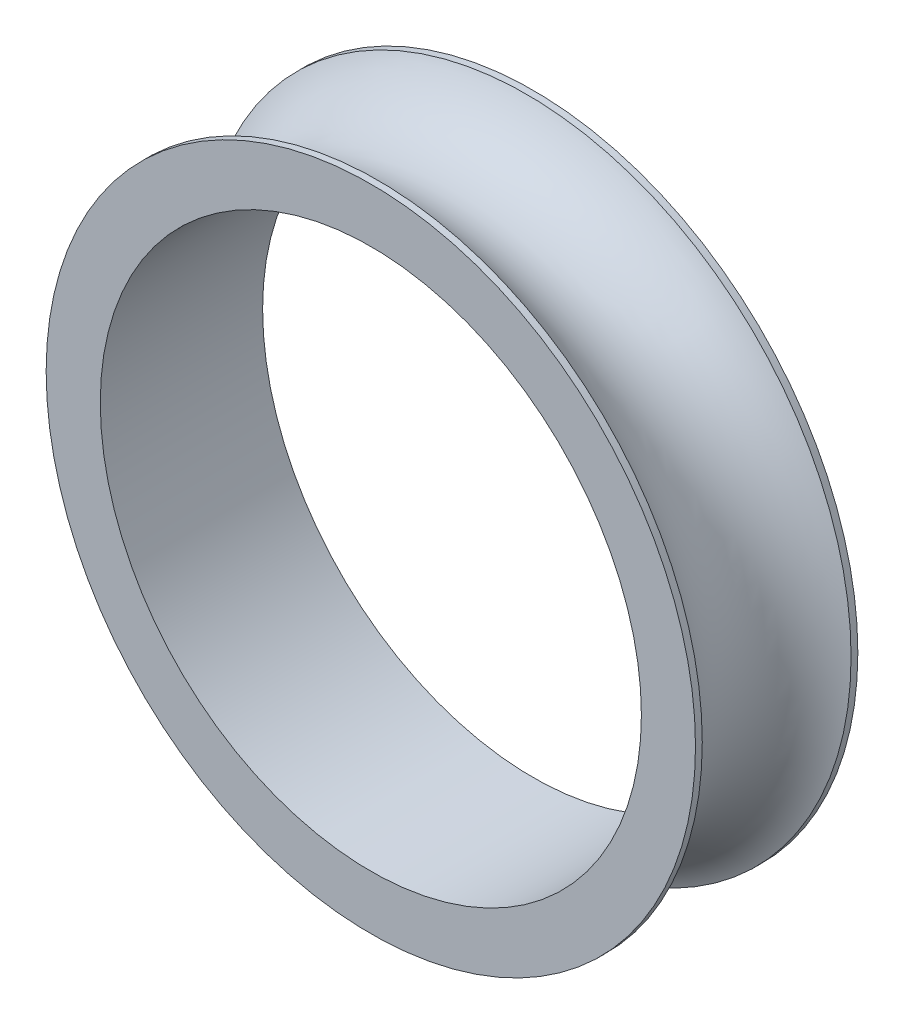
SolidWorks part; units mm, degrees
ref_plane "Front Plane" through (0, 0, 0) normal (0, 0, 1) x (1, 0, 0)
ref_plane "Top Plane" through (0, 0, 0) normal (0, 1, 0) x (1, 0, 0)
ref_plane "Right Plane" through (0, 0, 0) normal (1, 0, 0) x (0, 0, -1)
sketch "Sketch1" plane through (0, 0, 0) normal (0, 0, 1) x (1, 0, 0)
  circle A0 centre (0, 0) radius 25
  circle A1 centre (0, 0) radius 30
  dimension "D1" = 50
  dimension "D2" = 60
extrude "Boss-Extrude1" add sketch "Sketch1" along normal blind 15
sketch "Sketch2" plane through (0, 0, 0) normal (1, 0, 0) x (0, 0, -1)
  line L0 (-25.2577, 0) -> (16.1769, 0) construction
  line L1 (-7.5, 30) -> (-7.5, 36) construction
  line L2 (0, 30) -> (-15, 30) construction
  circle A0 centre (-7.5, 33) radius 7.5
  dimension "D1" = 15
  dimension "D2" = 3
revolve "Cut-Revolve1" cut sketch "Sketch2" angle 360 about L0
scale "Scale1" scale about centroid uniform scaling yes scale factor 1.9329
scale "Scale2" scale about centroid uniform scaling yes scale factor 1.5
